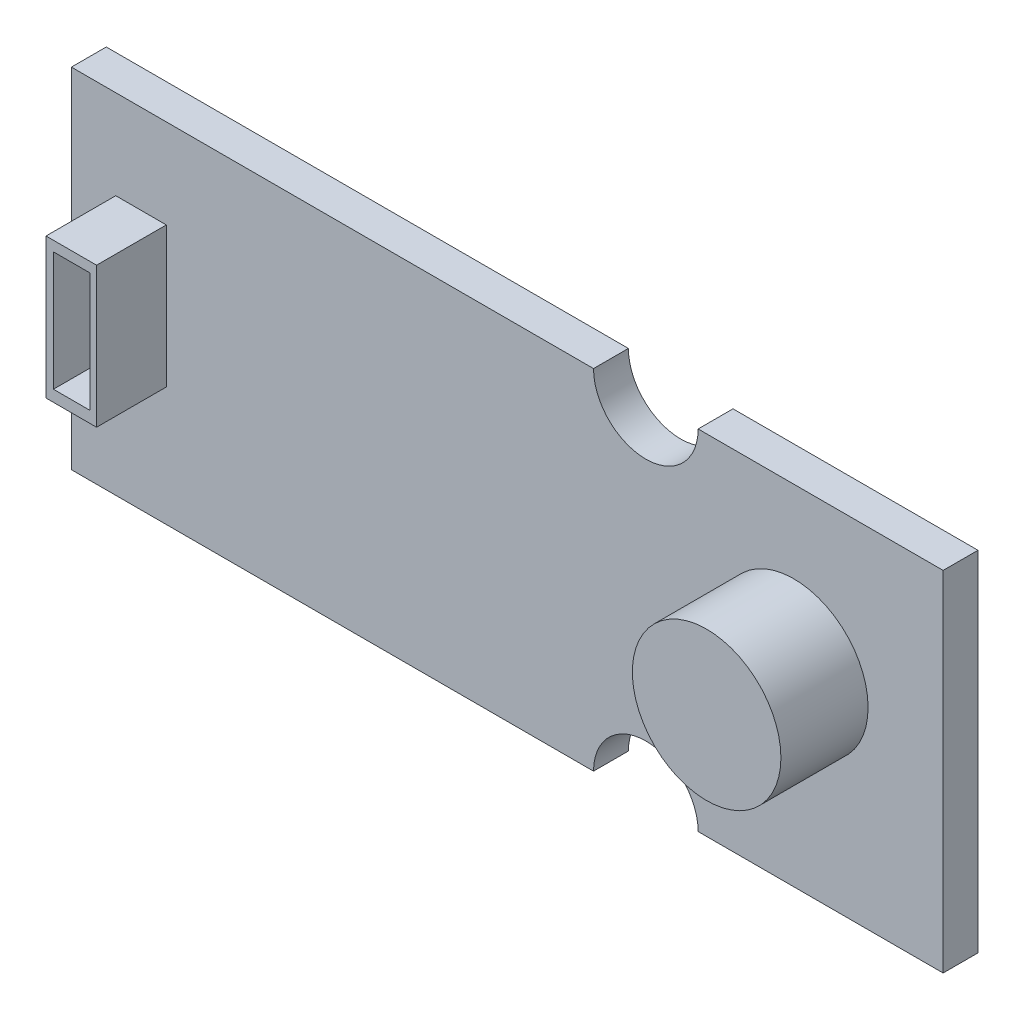
SolidWorks part; units mm, degrees
material "PE faible/moyenne densité"
ref_plane "Plan de face" through (0, 0, 0) normal (0, 0, 1) x (1, 0, 0)
ref_plane "Plan de dessus" through (0, 0, 0) normal (0, 1, 0) x (1, 0, 0)
ref_plane "Plan de droite" through (0, 0, 0) normal (1, 0, 0) x (0, 0, -1)
sketch "Esquisse1" plane through (0, 0, 0) normal (0, 0, 1) x (1, 0, 0)
  line L1 (-21.1115, 16.0714) -> (28.8885, 16.0714)
  line L2 (-21.1115, 16.0714) -> (-21.1115, -3.9286)
  line L3 (-21.1115, -3.9286) -> (28.8885, -3.9286)
  line L4 (28.8885, 16.0714) -> (28.8885, -3.9286)
  dimension "D1" = 50
  dimension "D2" = 20
extrude "Boss.-Extru.1" add sketch "Esquisse1" along normal blind 2
sketch "Esquisse2" plane through (0, 0, 2) normal (0, 0, 1) x (1, 0, 0)
  circle A0 centre (20.3239, 7.1131) radius 4.2607
extrude "Boss.-Extru.2" add sketch "Esquisse2" along normal blind 5
sketch "Esquisse3" plane through (0, 0, 2) normal (0, 0, 1) x (1, 0, 0)
  line L0 (28.8885, 16.0714) -> (-21.1115, 16.0714) construction
  line L1 (-21.1115, -3.9286) -> (28.8885, -3.9286) construction
  circle A0 centre (11.8361, 16.0714) radius 3
  circle A1 centre (11.8361, -3.9286) radius 3
  dimension "D1" = 6
extrude "Enlèv. mat.-Extru.1" cut sketch "Esquisse3" against normal blind 8
sketch "Esquisse4" plane through (0, 0, 2) normal (0, 0, 1) x (1, 0, 0)
  line L1 (-18.5685, 10.9543) -> (-15.6682, 10.9543)
  line L2 (-18.5685, 10.9543) -> (-18.5685, 2.9033)
  line L3 (-18.5685, 2.9033) -> (-15.6682, 2.9033)
  line L4 (-15.6682, 10.9543) -> (-15.6682, 2.9033)
extrude "Boss.-Extru.3" add sketch "Esquisse4" along normal blind 4
sketch "Esquisse5" plane through (0, 0, 6) normal (0, 0, 1) x (1, 0, 0)
  line L1 (-18.1427, 10.3801) -> (-16.0488, 10.3801)
  line L2 (-18.1427, 10.3801) -> (-18.1427, 3.5541)
  line L3 (-18.1427, 3.5541) -> (-16.0488, 3.5541)
  line L4 (-16.0488, 10.3801) -> (-16.0488, 3.5541)
extrude "Enlèv. mat.-Extru.2" cut sketch "Esquisse5" against normal blind 3
